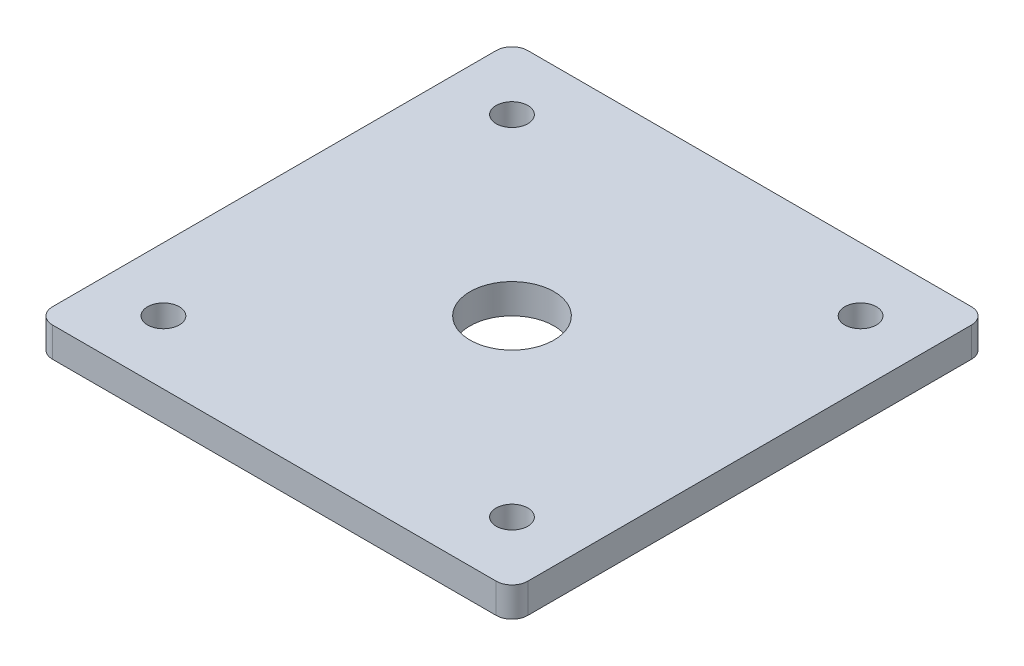
SolidWorks part; units mm, degrees
material "Acrylic (Medium-high impact)"
ref_plane "Front" through (0, 0, 0) normal (0, 0, 1) x (1, 0, 0)
ref_plane "Top" through (0, 0, 0) normal (0, 1, 0) x (1, 0, 0)
ref_plane "Right" through (0, 0, 0) normal (1, 0, 0) x (0, 0, -1)
sketch "Sketch1" plane through (0, 0, 0) normal (0, 0, 1) x (1, 0, 0)
  line L0 (-22.225, 0) -> (22.225, 0)
  dimension "D1" = 44.45
sketch "Sketch2" plane through (0, 0, 0) normal (0, 1, 0) x (1, 0, 0)
  line L0 (-13.97, 13.97) -> (13.97, 13.97) construction
  line L1 (-13.97, 13.97) -> (-13.97, -13.97) construction
  line L2 (-13.97, -13.97) -> (13.97, -13.97) construction
  line L3 (13.97, 13.97) -> (13.97, -13.97) construction
  line L4 (-13.97, 13.97) -> (13.97, -13.97) construction
  line L5 (-13.97, -13.97) -> (13.97, 13.97) construction
  line L7 (-19.05, 19.05) -> (19.05, 19.05)
  line L8 (-19.05, 19.05) -> (-19.05, -19.05)
  line L9 (-19.05, -19.05) -> (19.05, -19.05)
  line L10 (19.05, 19.05) -> (19.05, -19.05)
  line L11 (-19.05, 19.05) -> (19.05, -19.05) construction
  line L12 (-19.05, -19.05) -> (19.05, 19.05) construction
  circle A0 centre (-13.97, 13.97) radius 1.27
  circle A1 centre (-13.97, -13.97) radius 1.27
  circle A2 centre (13.97, -13.97) radius 1.27
  circle A3 centre (13.97, 13.97) radius 1.27
  circle A4 centre (0, 0) radius 3.3655
  point P0 (0, 0)
  point P12 (0, 0)
  dimension "D3" = 2.54
  dimension "D5" = 6.731
  dimension "D1" = 27.94
  dimension "D2" = 27.94
  dimension "D4" = 38.1
extrude "Boss-Extrude1" add sketch "Sketch2" along normal blind 2.3813
fillet "Fillet1" radius 1.27 4 edges at (-19.05, 1.1906, -19.05) (19.05, 1.1906, -19.05) (19.05, 1.1906, 19.05) (-19.05, 1.1906, 19.05)
pattern_linear "LPattern1" [suppressed] count 2 spacing 44.45 count 4 spacing 44.45
